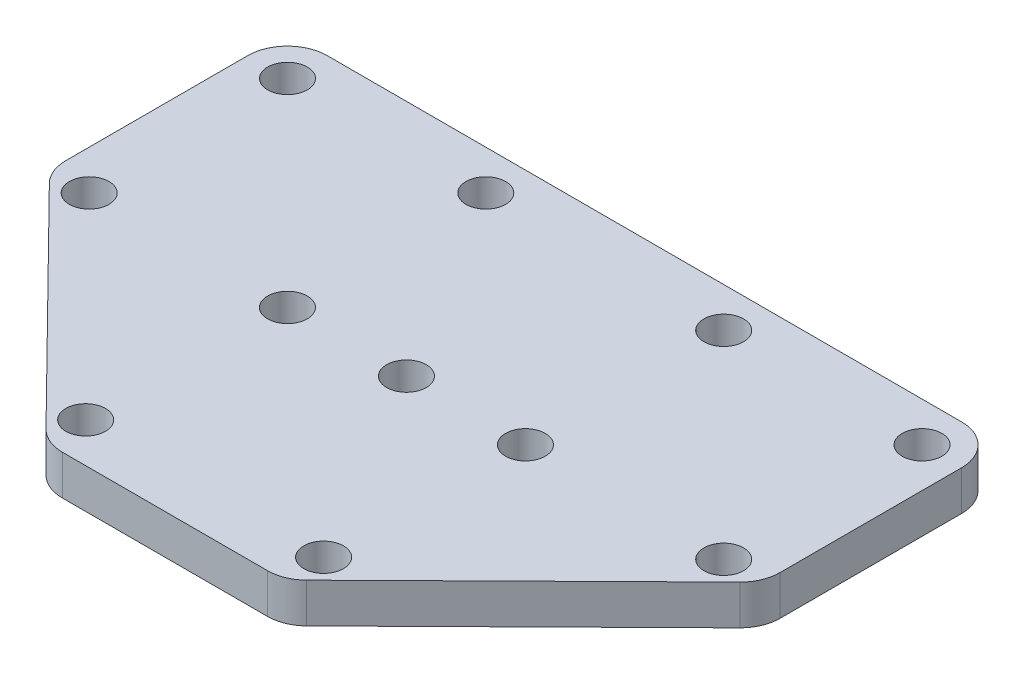
SolidWorks part; units mm, degrees
ref_plane "Front Plane" through (0, 0, 0) normal (0, 0, 1) x (1, 0, 0)
ref_plane "Top Plane" through (0, 0, 0) normal (0, 1, 0) x (1, 0, 0)
ref_plane "Right Plane" through (0, 0, 0) normal (1, 0, 0) x (0, 0, -1)
sketch "Sketch1" plane through (0, 0, 0) normal (0, 1, 0) x (1, 0, 0)
  line L0 (-131.4715, 109.2313) -> (71.7285, 109.2313)
  line L2 (-63.8418, -43.1687) -> (1.8361, -43.1687)
  line L4 (-144.1715, 96.5313) -> (-144.1715, 38.2334)
  line L5 (-140.5221, 29.3241) -> (-72.8924, -39.378)
  line L6 (84.4285, 96.5313) -> (84.4285, 38.3496)
  line L7 (80.639, 29.3) -> (10.7465, -39.5182)
  arc A4 (-140.5221, 29.3241) -> (-144.1715, 38.2334) centre (-131.4715, 38.2334) cw
  arc A5 (-63.8418, -43.1687) -> (-72.8924, -39.378) centre (-63.8418, -30.4687) cw
  arc A6 (10.7465, -39.5182) -> (1.8361, -43.1687) centre (1.8361, -30.4687) cw
  arc A7 (84.4285, 38.3496) -> (80.639, 29.3) centre (71.7285, 38.3496) cw
  arc A8 (84.4285, 96.5313) -> (71.7285, 109.2313) centre (71.7285, 96.5313) ccw
  arc A9 (-131.4715, 109.2313) -> (-144.1715, 96.5313) centre (-131.4715, 96.5313) ccw
  point P4 (-144.1715, 33.0313)
  point P12 (-69.161, -43.1687)
  point P16 (7.039, -43.1687)
  point P19 (84.4285, 33.0313)
  point P22 (84.4285, 109.2313)
  point P25 (-144.1715, 109.2313)
  dimension "D1" = 76.2
  dimension "D2" = 76.2
  dimension "D5" = 12.7
  dimension "D3" = 228.6
  dimension "D4" = 76.2
  dimension "D6" = 152.4
extrude "Boss-Extrude1" add sketch "Sketch1" along normal blind 12.7
sketch "Sketch2" plane through (0, 12.7, 0) normal (0, 1, 0) x (1, 0, 0)
  line L2 (71.7285, 109.2313) -> (-131.4715, 109.2313) construction
  line L3 (-144.1715, 96.5313) -> (-144.1715, 38.2334) construction
  line L4 (84.4285, 38.3496) -> (84.4285, 96.5313) construction
  line L5 (-63.8418, -43.1687) -> (1.8361, -43.1687) construction
  circle A2 centre (-69.1029, -30.4687) radius 6.35
  circle A3 centre (7.0971, -30.4687) radius 6.35
  circle A4 centre (-67.9715, 96.5313) radius 6.35
  circle A5 centre (8.2285, 96.5313) radius 6.35
  circle A6 centre (-67.9715, 33.0213) radius 6.35
  circle A7 centre (8.2285, 33.0313) radius 6.35
  circle A8 centre (-131.4715, 96.5313) radius 6.35
  circle A9 centre (-131.4715, 33.0313) radius 6.35
  circle A10 centre (71.7285, 96.5313) radius 6.35
  circle A11 centre (71.7285, 33.0313) radius 6.35
  circle A12 centre (-29.8715, 33.0313) radius 6.35
  dimension "D1" = 12.7
  dimension "D2" = 12.7
  dimension "D5" = 38.1
  dimension "D16" = 12.7
  dimension "D15" = 12.7
  dimension "D3" = 76.2
  dimension "D4" = 63.5
  dimension "D6" = 76.2
  dimension "D7" = 12.7
  dimension "D8" = 76.2
  dimension "D9" = 76.2
  dimension "D10" = 63.5
  dimension "D11" = 63.5
  dimension "D12" = 12.7
  dimension "D13" = 63.5
  dimension "D14" = 12.7
  dimension "D17" = 12.7
  dimension "D18" = 12.7
  dimension "D19" = 12.7
  dimension "D20" = 63.5
extrude "Cut-Extrude1" cut sketch "Sketch2" against normal through all
